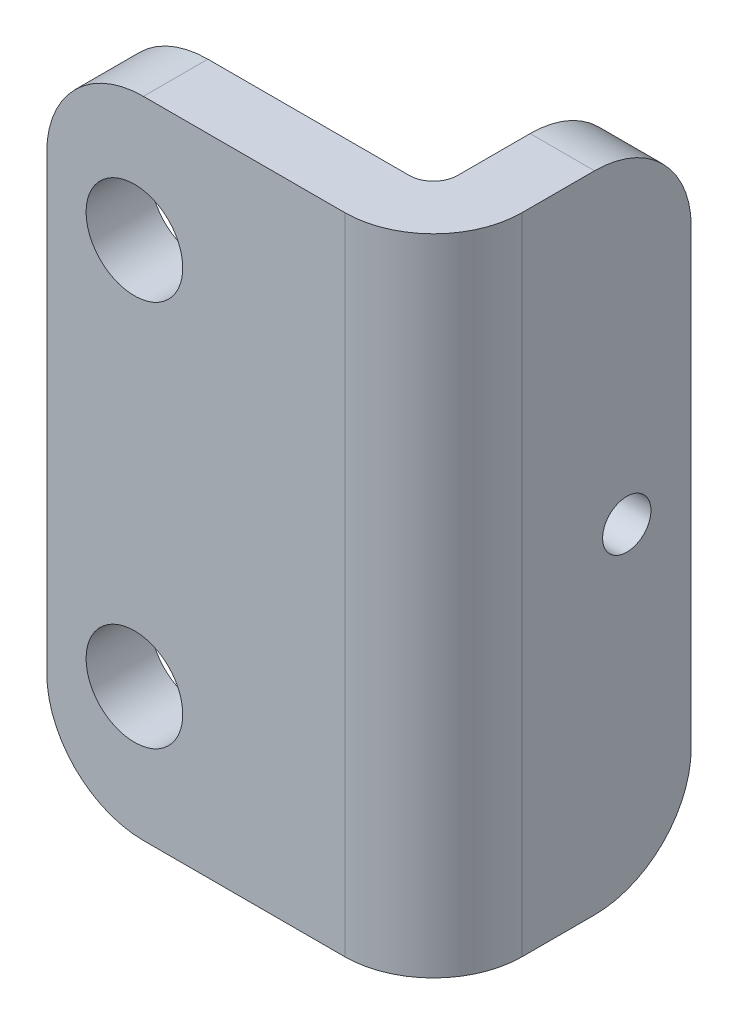
SolidWorks part; units mm, degrees
ref_plane "Front Plane" through (0, 0, 0) normal (0, 0, 1) x (1, 0, 0)
ref_plane "Top Plane" through (0, 0, 0) normal (0, 1, 0) x (1, 0, 0)
ref_plane "Right Plane" through (0, 0, 0) normal (1, 0, 0) x (0, 0, -1)
sketch "Sketch2" plane through (0, 0, 0) normal (0, 1, 0) x (1, 0, 0)
  line L0 (0, 9.46) -> (0, -7.6979) construction
  line L1 (-10.1513, 0) -> (9.9189, 0) construction
  line L2 (-1, 7) -> (1, 7)
  line L3 (1, 7) -> (1, 1.75)
  line L4 (-1.75, -1) -> (-11, -1)
  line L5 (-11, -1) -> (-11, 1)
  line L6 (-11, 1) -> (-1.75, 1)
  line L7 (-1, 1.75) -> (-1, 7)
  arc A0 (-1.75, 1) -> (-1, 1.75) centre (-1.75, 1.75) ccw
  arc A1 (1, 1.75) -> (-1.75, -1) centre (-1.75, 1.75) cw
  dimension "D5" = 0.75
  dimension "D6" = 2.75
  dimension "D1" = 2
  dimension "D2" = 1
  dimension "D3" = 2
  dimension "D4" = 1
  dimension "D7" = 12
  dimension "D8" = 8
extrude "Boss-Extrude1" add sketch "Sketch2" along normal blind 20
fillet "Fillet1" radius 3 4 edges at (0, 0, -7) (0, 20, -7) (-11, 20, 0) (-11, 0, 0)
sketch "Sketch3" plane through (0, 0, -1) normal (0, 0, -1) x (-1, 0, 0)
  line L0 (11, 10) -> (-11.7333, 10) construction
  line L1 (11, 17) -> (11, 3) construction
  line L2 (-1, 17) -> (-1, 3) construction
  circle A0 centre (8.28, 16) radius 1.5
  circle A1 centre (8.28, 4) radius 1.5
  dimension "D1" = 3
  dimension "D3" = 6
  dimension "D2" = 12
  dimension "D4" = 9.28
extrude "Cut-Extrude1" cut sketch "Sketch3" against normal through all
sketch "Sketch4" plane through (-1, 0, 0) normal (-1, 0, 0) x (0, 0, 1)
  line L0 (-7, 17) -> (-7, 3) construction
  circle A0 centre (-5, 10) radius 0.75
  dimension "D1" = 1.5
  dimension "D2" = 2
extrude "Cut-Extrude2" cut sketch "Sketch4" against normal through all
scale "Scale1" scale about centroid uniform scaling yes scale factor 1.9
